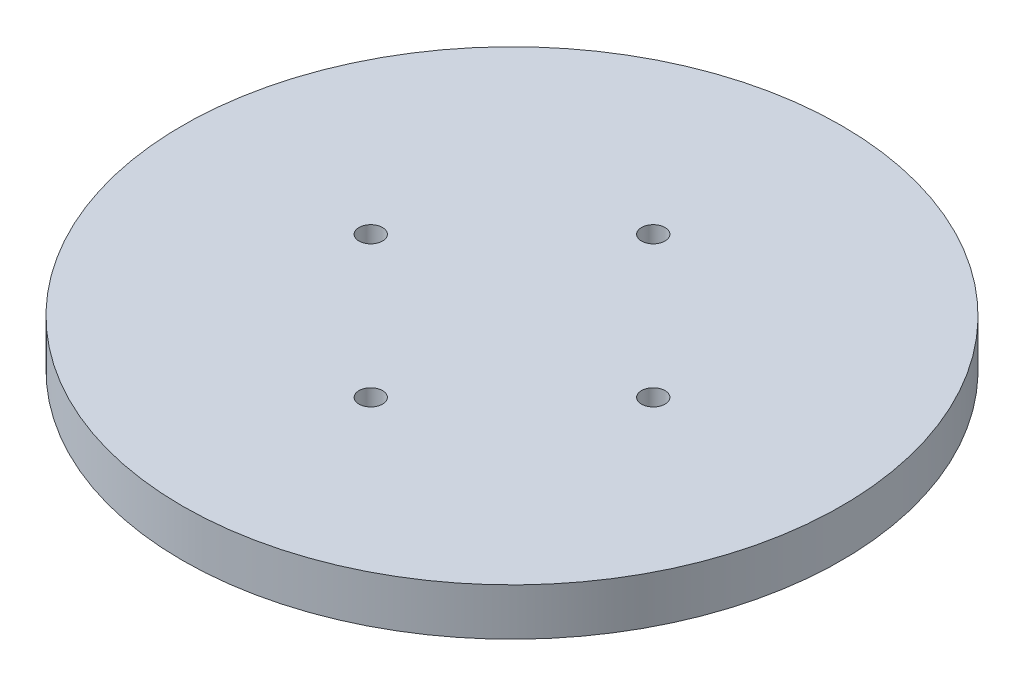
SolidWorks part; units mm, degrees
ref_plane "Alzado" through (0, 0, 0) normal (0, 0, 1) x (1, 0, 0)
ref_plane "Planta" through (0, 0, 0) normal (0, 1, 0) x (1, 0, 0)
ref_plane "Vista lateral" through (0, 0, 0) normal (1, 0, 0) x (0, 0, -1)
sketch "Croquis1" plane through (0, 0, 0) normal (0, 1, 0) x (1, 0, 0)
  line L0 (0, 0) -> (0, 30) construction
  circle A0 centre (0, 0) radius 70
  circle A1 centre (0, 30) radius 2.5
  circle A2 centre (30, 0) radius 2.5
  circle A3 centre (0, -30) radius 2.5
  circle A4 centre (-30, 0) radius 2.5
  dimension "D1" = 140
  dimension "D2" = 5
  dimension "D3" = 30
  dimension "D4" = 4
extrude "Saliente-Extruir1" add sketch "Croquis1" along normal blind 10
